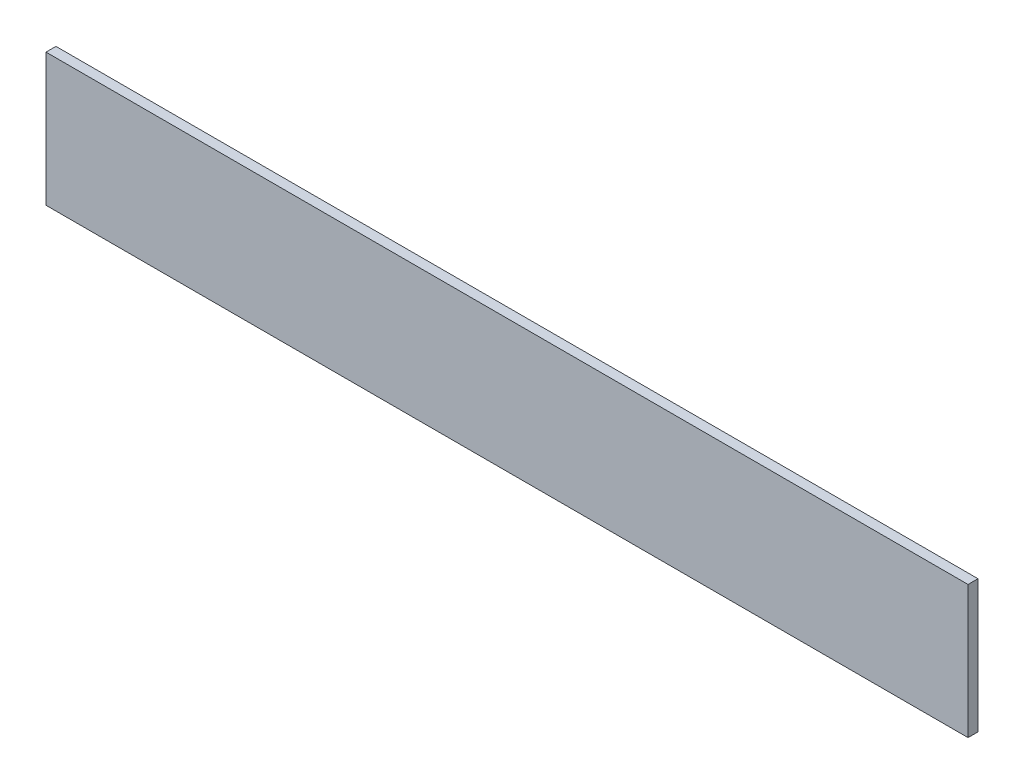
SolidWorks part; units mm, degrees
material "Balsa"
ref_plane "Alzado" through (0, 0, 0) normal (0, 0, 1) x (1, 0, 0)
ref_plane "Planta" through (0, 0, 0) normal (0, 1, 0) x (1, 0, 0)
ref_plane "Vista lateral" through (0, 0, 0) normal (1, 0, 0) x (0, 0, -1)
sketch "Croquis1" plane through (0, 0, 0) normal (0, 0, 1) x (1, 0, 0)
  line L1 (0, 0) -> (556, 0)
  line L2 (0, 0) -> (0, 80)
  line L3 (0, 80) -> (556, 80)
  line L4 (556, 0) -> (556, 80)
  dimension "D1" = 556
  dimension "D2" = 80
extrude "Saliente-Extruir1" add sketch "Croquis1" along normal blind 6
